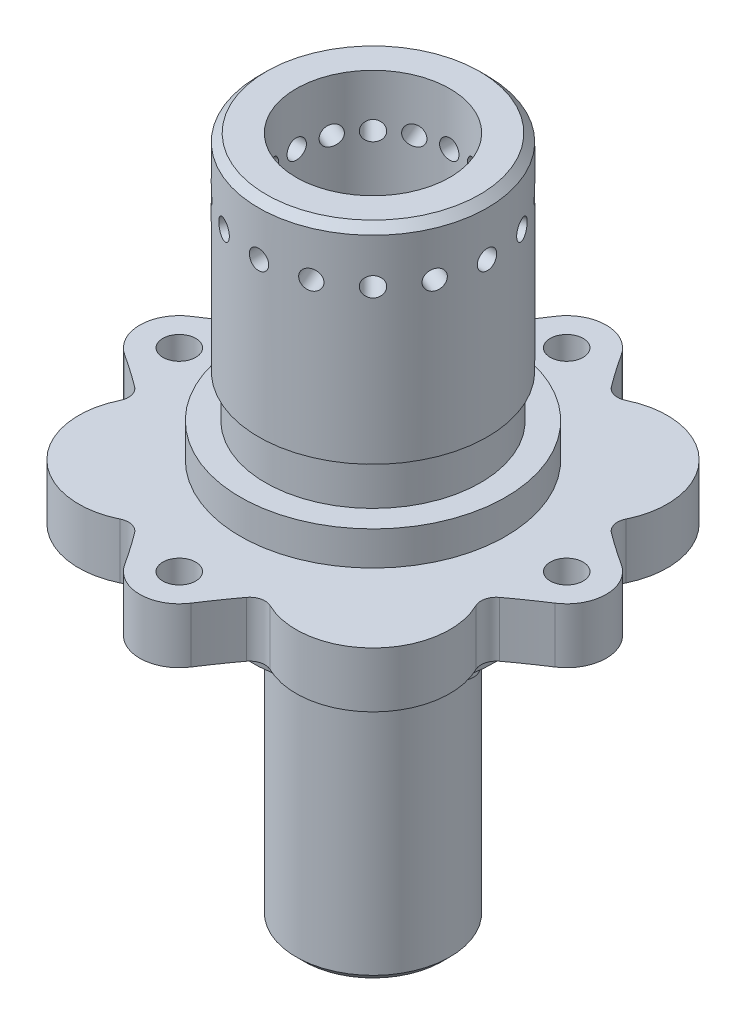
SolidWorks part; units mm, degrees
material "7075-T6 (SN)"
ref_plane "X-Y Datum" through (0, 0, 0) normal (0, 0, 1) x (1, 0, 0)
ref_plane "X-Z Datum" through (0, 0, 0) normal (0, 1, 0) x (1, 0, 0)
ref_plane "Y-Z Datum" through (0, 0, 0) normal (1, 0, 0) x (0, 0, -1)
sketch "Sketch1" plane through (0, 0, 0) normal (1, 0, 0) x (0, 0, -1)
  line L0 (0, 0) -> (-50000, 0) construction
  line L1 (0, 0) -> (0, 50000) construction
  line L2 (0, 0) -> (-27.2547, 0)
  line L3 (-27.2547, 0) -> (-25.0825, -12.319)
  line L4 (-25.0825, -12.319) -> (-25.0825, -17.0815)
  line L5 (-25.0825, -17.0815) -> (-15.875, -17.0815)
  line L8 (0, -71.1505) -> (0, 0)
  line L9 (0, -71.1505) -> (-14.2875, -71.1505)
  line L10 (-15.875, -17.0815) -> (-15.875, -69.563)
  line L11 (-14.2875, -71.1505) -> (-15.875, -69.563)
  dimension "D1" = 12.319
  dimension "D2" = 4.7625
  dimension "D3" = 54.069
  dimension "D4" = 50.165
  dimension "D5" = 45
  dimension "D6" = 80
  dimension "D7" = 31.75
  dimension "D8" = 1.5875
sketch "Sketch2" plane through (0, 0, 0) normal (1, 0, 0) x (0, 0, -1)
  line L0 (0, 0) -> (-52.5, 0)
  line L1 (200000, 0) -> (-250000, 0) construction
  line L2 (-52.5, 0) -> (-52.5, 11.43)
  line L3 (-52.5, 11.43) -> (-27.4096, 11.43)
  line L4 (-27.4096, 11.43) -> (-27.4096, 18.43)
  line L5 (-27.4096, 18.43) -> (-22.225, 18.43)
  line L6 (-22.225, 18.43) -> (-22.225, 27.305)
  line L7 (-22.225, 27.305) -> (-23.6195, 27.305)
  line L10 (0, -200000) -> (0, 250000) construction
  line L11 (0, 69.85) -> (0, 0)
  line L15 (0, 69.85) -> (-22.032, 69.85)
  line L16 (-22.032, 69.85) -> (-23.6195, 68.2625)
  line L17 (-23.6195, 68.2625) -> (-23.6195, 27.305)
  line L18 (0, 0) -> (-50000, 0) construction
  line L19 (0, 0) -> (0, 50000) construction
  line L20 (0, 0) -> (0, -31242.0183) construction
  dimension "D1" = 11.43
  dimension "D2" = 58.42
  dimension "D3" = 47.2389
  dimension "D4" = 1.5875
  dimension "D5" = 45
  dimension "D6" = 54.8192
  dimension "D7" = 105
  dimension "D8" = 7
  dimension "D9" = 40.9575
  dimension "D10" = 44.45
revolve "Bearing Shaft/Flange Support" add sketch "Sketch1" angle 360 about L1
revolve "Drive Pin Support" add sketch "Sketch2" angle 360 about L19
sketch "Sketch5" plane through (0, 0, 0) normal (1, 0, 0) x (0, 0, -1)
  line L0 (0, 69.85) -> (15.875, 69.85)
  line L1 (22.032, 69.85) -> (-22.032, 69.85) construction
  line L4 (15.875, -9.525) -> (0, -9.525)
  line L5 (0, -9.525) -> (0, 69.85)
  line L6 (0, 0) -> (-50000, 0) construction
  line L7 (15.875, -9.525) -> (15.875, 69.85)
  line L8 (0, 0) -> (0, -50000) construction
  dimension "D1" = 79.375
  dimension "D4" = 31.75
revolve "Center Mass Removal" cut sketch "Sketch5" angle 360 about L8
hole_wizard "Drive Pin Holes" positions "Sketch6" profile "Sketch7" tap size "M8x1.25" standard "ANSI Metric" end condition through all
sketch "Sketch6" plane through (0, 0, 0) normal (0, -1, 0) x (-1, 0, 0)
  circle A0 centre (0, 0) radius 40 construction
  point P0 (0, -40)
  dimension "D1" = 80
sketch "Sketch7" plane through (0, 0, 40) normal (1, 0, 0) x (0, 0, -1)
  line L0 (0, 0) -> (0, 69.85)
  line L1 (0, 69.85) -> (3.4, 69.85)
  line L2 (3.4, 69.85) -> (3.4, 0)
  line L5 (3.4, 0) -> (0, 0)
  line L11 (0, -6.35) -> (0, 107.95) construction
  dimension "Thru Tap Drill Dia." = 6.8
  dimension "Thru Tap Drill Depth" = 69.85
cosmetic thread "Hole Thread1" parameters "D2"=8
pattern_circular "Drive Pin Holes Pattern" count 4 over 360 about axis through (0, 0, 0) along (0, 1, 0) of "Drive Pin Holes"
cosmetic thread "Hole Thread2" parameters "D2"=8
cosmetic thread "Hole Thread3" parameters "D2"=8
cosmetic thread "Hole Thread4" parameters "D2"=8
sketch "Sketch8" plane through (0, 0, 0) normal (0, -1, 0) x (1, 0, 0)
  line L0 (0, 0) -> (-64.0279, 64.0279) construction
  line L1 (0, 0) -> (0, 72.7145) construction
  arc A0 (6.8518, 44.4362) -> (-6.8518, 44.4362) centre (0, 40) ccw
  arc A1 (6.8518, 44.4362) -> (13.2749, 35.4052) centre (113.4583, 113.4583) ccw
  arc A2 (44.4362, -6.8518) -> (44.4362, 6.8518) centre (40, 0) ccw
  arc A3 (44.4362, -6.8518) -> (44.4362, 6.8518) centre (40, 0) ccw
  arc A5 (44.4362, -6.8518) -> (35.4052, -13.2749) centre (113.4583, -113.4583) ccw
  circle A7 centre (0, 40) radius 3.4 construction
  circle A8 centre (0, 0) radius 52.5 construction
  circle A9 centre (0, 0) radius 40 construction
  arc A10 (-6.8518, -44.4362) -> (6.8518, -44.4362) centre (0, -40) ccw
  arc A11 (-6.8518, -44.4362) -> (6.8518, -44.4362) centre (0, -40) ccw
  arc A13 (-44.4362, 6.8518) -> (-44.4362, -6.8518) centre (-40, 0) ccw
  arc A14 (-44.4362, 6.8518) -> (-44.4362, -6.8518) centre (-40, 0) ccw
  arc A15 (-44.4362, 6.8518) -> (-35.4052, 13.2749) centre (-113.4583, 113.4583) ccw
  arc A16 (6.8518, 44.4362) -> (-6.8518, 44.4362) centre (0, 40) ccw
  circle A17 centre (0, 0) radius 52.5
  arc A18 (-6.8518, -44.4362) -> (-13.2749, -35.4052) centre (-113.4583, -113.4583) ccw
  arc A19 (-169.6965, 0.4112) -> (0.4112, -169.6965) centre (-113.4583, -113.4583) ccw [skipped]
  arc A20 (-13.2749, 35.4052) -> (-35.4052, 13.2749) centre (-22.4506, 22.4506) ccw
  arc A21 (-13.2749, 35.4052) -> (-6.8518, 44.4362) centre (-113.4583, 113.4583) ccw
  arc A22 (35.4052, 13.2749) -> (13.2749, 35.4052) centre (22.4506, 22.4506) ccw
  arc A23 (13.2749, -35.4052) -> (35.4052, -13.2749) centre (22.4506, -22.4506) ccw
  arc A24 (-35.4052, -13.2749) -> (-13.2749, -35.4052) centre (-22.4506, -22.4506) ccw
  arc A25 (35.4052, 13.2749) -> (44.4362, 6.8518) centre (113.4583, 113.4583) ccw
  arc A26 (13.2749, -35.4052) -> (6.8518, -44.4362) centre (113.4583, -113.4583) ccw
  arc A27 (-35.4052, -13.2749) -> (-44.4362, -6.8518) centre (-113.4583, -113.4583) ccw
  point P49 (0, 0)
  circle M10 centre (0, 0) radius 52.5
  dimension "D1" = 4.7625
  dimension "D2" = 45
  dimension "D3" = 254
  dimension "D4" = 80
  dimension "D6" = 31.75
  dimension "D7" = 31.75
  dimension "D5" = 4
  dimension "D8" = 4
extrude "Flange Support Cut" cut sketch "Sketch8" against normal up to next contours A10 A18 A13 A15 A0 A1 A2 A5 M10
sketch "Sketch10" plane through (0, -17.0815, 0) normal (0, -1, 0) x (1, 0, 0)
  line L0 (0, 0) -> (0, 50000) construction
  line L1 (10.6319, -18.415) -> (21.2638, 0)
  line L2 (21.2638, 0) -> (10.6319, 18.415)
  line L3 (10.6319, 18.415) -> (-10.6319, 18.415)
  line L4 (-10.6319, 18.415) -> (-21.2638, 0)
  line L5 (-21.2638, 0) -> (-10.6319, -18.415)
  line L6 (-10.6319, -18.415) -> (10.6319, -18.415)
  line L7 (0, 0) -> (50000, 0) construction
  circle A0 centre (0, 0) radius 18.415 construction
  circle A1 centre (0, 0) radius 25.0825 construction
  circle A2 centre (0, 0) radius 25.0825
  point P17 (0, 18.415)
  dimension "D1" = 36.83
extrude "Brake Hat Hex" cut sketch "Sketch10" against normal blind 4.7625
sketch "Sketch11" plane through (0, -71.1505, 0) normal (0, -1, 0) x (1, 0, 0)
  circle A25 centre (0, 0) radius 9.525 construction
  circle A26 centre (0, 9.525) radius 3.175
  circle A27 centre (8.2489, 4.7625) radius 3.175
  circle A28 centre (8.2489, -4.7625) radius 3.175
  circle A29 centre (0, -9.525) radius 3.175
  circle A30 centre (-8.2489, -4.7625) radius 3.175
  circle A31 centre (-8.2489, 4.7625) radius 3.175
  dimension "D1" = 19.05
  dimension "D2" = 6.35
  dimension "D3" = 6
hole_wizard "5/16 Clearance Hole1" positions "Sketch12" profile "Sketch13" hole size "5/16" standard "ANSI Inch" end condition through all
sketch "Sketch12" plane through (0, -71.1505, 0) normal (0, -1, 0) x (-1, 0, 0)
  point P0 (0, 0)
sketch "Sketch13" plane through (0, -71.1505, 0) normal (1, 0, 0) x (0, 0, -1)
  line L0 (0, 0) -> (0, 141.0005)
  line L1 (0, 141.0005) -> (4.2164, 141.0005)
  line L2 (4.2164, 141.0005) -> (4.2164, 0)
  line L5 (4.2164, 0) -> (0, 0)
  line L11 (0, -6.35) -> (0, 107.95) construction
  dimension "Thru Hole Dia." = 8.4328
  dimension "Thru Hole Depth" = 141.0005
fillet "Brake Hat Fillet" [suppressed] radius 3.175
fillet "Hub Fillet" [suppressed] radius 0.7937
sketch "Sketch14" plane through (0, 0, 0) normal (1, 0, 0) x (0, 0, -1)
  line L0 (22.032, 69.85) -> (-22.032, 69.85) construction
  line L1 (0, 0) -> (-50000, 0) construction
  line L2 (0, 0) -> (0, -50000) construction
  circle A0 centre (0, 59.05) radius 2
  dimension "D2" = 4
  dimension "D1" = 10.8
extrude "Pin Holes" cut sketch "Sketch14" against normal through all
pattern_circular "Pin Hole Pattern" count 16 over 360 about axis through (0, 0, 0) along (0, -1, 0) of "Pin Holes"
chamfer "Floral Pattern Chamfer" [suppressed] distance 3.175 angle 45
sketch3d "3DSketch2"
  line L0 (0, 0, 0) -> (0, 0, -205.74)
  line L1 (0, 0, -205.74) -> (25.4, 0, -205.74)
  line L2 (0, 0, -205.74) -> (0, -25.4, -205.74)
  dimension "D1" = 25.4
  dimension "D2" = 25.4
  dimension "D3" = 205.74
extrude "Tripod Pins" [suppressed] cut sketch "Sketch11" against normal blind 12.7
fillet "Flange Fillet" [suppressed] radius 1.27
sketch "Sketch15" plane through (0, 0, 0) normal (0, -1, 0) x (1, 0, 0)
  circle A0 centre (0, 0) radius 40 construction
  dimension "D1" = 80
thread "Thread1" [suppressed] pitch 2.1167 start angle 0, offset 0.3048, length 0, pitch 2.1167, diameter 47.625
ref_plane "Plane1" through (-23.8125, 70.1548, 0) normal (0, 0, 1) x (-1, 0, 0)
sketch "Thread Profile1" plane through (-23.8125, 70.1548, 0) normal (0, 0, 1) x (-1, 0, 0)
  line L0 (0, 0) -> (0, 2.1167) construction
  line L11 (0, 0) -> (0, 1.8521)
  line L12 (0, 1.8521) -> (-1.1457, 1.1906)
  line L13 (-1.1457, 1.1906) -> (-1.1457, 0.6615)
  line L15 (-1.1457, 0.6615) -> (0, 0)
  line L17 (-1.1457, 0.926) -> (0, 0.926) construction
  point P2 (0, 0)
  dimension "Pitch" = 2.1167
  dimension "Profile_Angle" = 60
  dimension "Profile_Land" = 0.5292
  dimension "Profile_Height" = 1.1457
fillet "Fillet1" radius 3.175 8 edges at (-13.2749, 5.715, 35.4052) (-35.4052, 5.715, 13.2749) (-35.4052, 5.715, -13.2749) (-13.2749, 5.715, -35.4052) (13.2749, 5.715, -35.4052) (35.4052, 5.715, -13.2749) (35.4052, 5.715, 13.2749) (13.2749, 5.715, 35.4052)
fillet "Fillet2" radius 3.175 6 edges at (-21.2638, -14.7003, 0) (-10.6319, -14.7003, -18.415) (10.6319, -14.7003, -18.415) (21.2638, -14.7003, 0) (10.6319, -14.7003, 18.415) (-10.6319, -14.7003, 18.415)
